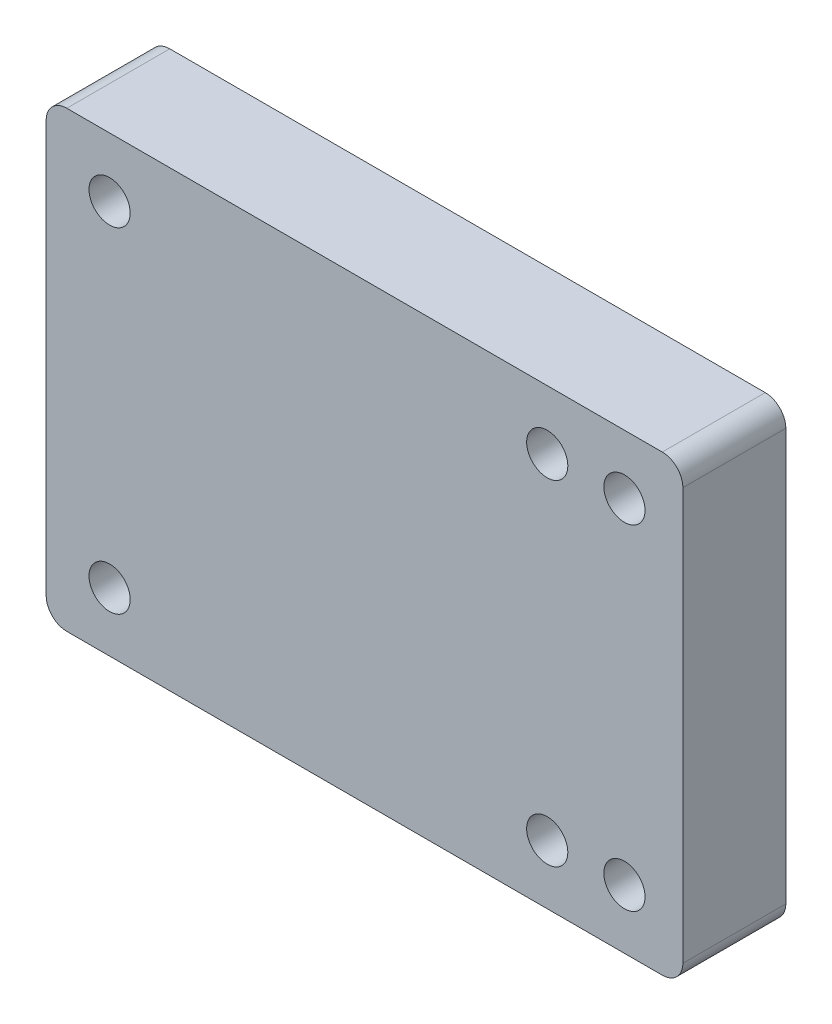
SolidWorks part; units mm, degrees
ref_plane "Front Plane" through (0, 0, 0) normal (0, 0, 1) x (1, 0, 0)
ref_plane "Top Plane" through (0, 0, 0) normal (0, 1, 0) x (1, 0, 0)
ref_plane "Right Plane" through (0, 0, 0) normal (1, 0, 0) x (0, 0, -1)
sketch "Sketch1" plane through (0, 0, 0) normal (0, 0, 1) x (1, 0, 0)
  line L0 (44.1799, 75.1) -> (44.1799, 125.9)
  line L18 (46.7234, 72.56) -> (120.1675, 72.56)
  line L19 (122.7075, 75.1) -> (122.7075, 125.9)
  line L20 (120.1675, 128.44) -> (46.7234, 128.44)
  line L34 (46.7234, 72.56) -> (120.1675, 72.56)
  line L35 (122.7075, 75.1) -> (122.7075, 125.9)
  line L36 (120.1675, 128.44) -> (46.7234, 128.44)
  arc A4 (120.1675, 72.56) -> (122.7075, 75.1) centre (120.1675, 75.1) ccw
  arc A5 (122.7075, 125.9) -> (120.1675, 128.44) centre (120.1675, 125.9) ccw
  arc A8 (120.1675, 72.56) -> (122.7075, 75.1) centre (120.1675, 75.1) ccw
  arc A9 (122.7075, 125.9) -> (120.1675, 128.44) centre (120.1675, 125.9) ccw
  circle A14 centre (105.9781, 79.8625) radius 2.54
  circle A15 centre (115.5031, 79.8625) radius 2.54
  circle A16 centre (115.5031, 121.1375) radius 2.54
  circle A17 centre (105.9781, 121.1375) radius 2.54
  circle A18 centre (52.0031, 121.1375) radius 2.54
  circle A19 centre (52.0031, 79.8625) radius 2.54
  ellipse E13 centre (46.7234, 75.1) end of major axis (49.2669, 75.1) minor radius 2.54 (44.1799, 75.1) -> (46.7234, 72.56) ccw
  ellipse E14 centre (46.7234, 125.9) end of major axis (49.2669, 125.9) minor radius 2.54 (46.7234, 128.44) -> (44.1799, 125.9) ccw
  ellipse E25 centre (46.7234, 75.1) end of major axis (49.2669, 75.1) minor radius 2.54 (44.1799, 75.1) -> (46.7234, 72.56) ccw
  ellipse E26 centre (46.7234, 125.9) end of major axis (49.2669, 125.9) minor radius 2.54 (46.7234, 128.44) -> (44.1799, 125.9) ccw
extrude "Boss-Extrude1" add sketch "Sketch1" along normal blind 12.7 contours L20 E14 L0 E13 L18 A4 L19 A5 A14 A15 A16 A17 A18 A19
